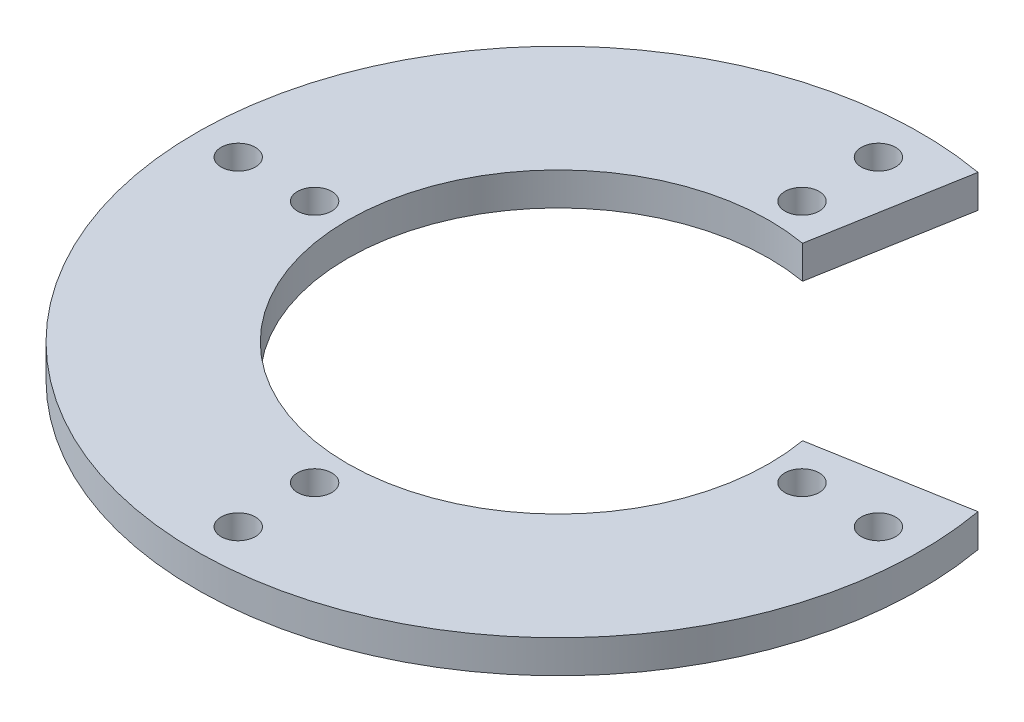
SolidWorks part; units mm, degrees
ref_plane "Front Plane" through (0, 0, 0) normal (0, 0, 1) x (1, 0, 0)
ref_plane "Top Plane" through (0, 0, 0) normal (0, 1, 0) x (1, 0, 0)
ref_plane "Right Plane" through (0, 0, 0) normal (1, 0, 0) x (0, 0, -1)
sketch "Sketch1" plane through (0, 0, 0) normal (0, 1, 0) x (1, 0, 0)
  line L0 (0, 18.5) -> (0, 0) construction
  line L1 (0, 0) -> (4.7753, 27.0822)
  line L2 (0, 0) -> (27.0822, 4.7753)
  line L3 (0, 0) -> (24.1467, 24.1467) construction
  line L4 (0, 0) -> (39.76, 0) construction
  circle A0 centre (0, 0) radius 18.5 construction
  circle A1 centre (0, 18.5) radius 1.3
  circle A2 centre (0, 0) radius 24.3 construction
  circle A3 centre (0, 24.3) radius 1.3
  circle A4 centre (0, 0) radius 27.5
  circle A5 centre (0, 0) radius 16
  circle A6 centre (18.5, 0) radius 1.3
  circle A7 centre (24.3, 0) radius 1.3
  circle A8 centre (0, -18.5) radius 1.3
  circle A9 centre (0, -24.3) radius 1.3
  circle A10 centre (-18.5, 0) radius 1.3
  circle A11 centre (-24.3, 0) radius 1.3
  point P28 (0, 0)
  dimension "D1" = 2.6
  dimension "D2" = 37
  dimension "D3" = 48.6
  dimension "D4" = 55
  dimension "D5" = 32
  dimension "D7" = 45
  dimension "D8" = 70
  dimension "D6" = 4
extrude "Boss-Extrude1" add sketch "Sketch1" along normal blind 2.5 contours A5 L1 A4 L2 A11 A10 A9 A8 A7 A6 A1 A3
